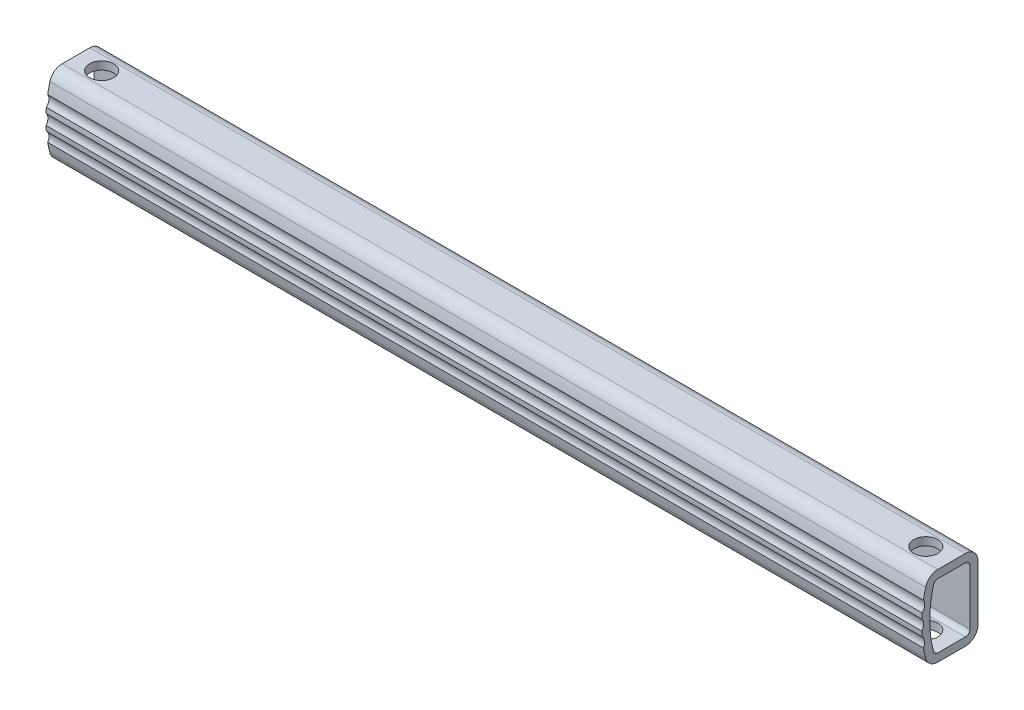
SolidWorks part; units mm, degrees
ref_plane "Front Plane" through (0, 0, 0) normal (0, 0, 1) x (1, 0, 0)
ref_plane "Top Plane" through (0, 0, 0) normal (0, 1, 0) x (1, 0, 0)
ref_plane "Right Plane" through (0, 0, 0) normal (1, 0, 0) x (0, 0, -1)
sketch "Sketch1" plane through (0, 0, 0) normal (1, 0, 0) x (0, 0, -1)
  line L0 (0, 0) -> (-81.198, 0) construction
  line L1 (-1.716, 5) -> (1.716, 5)
  line L2 (3.284, 3.432) -> (3.284, -3.432)
  line L3 (-1.716, -5) -> (1.716, -5)
  line L4 (11.2701, 0) -> (-3.9571, 4.0242) construction
  line L5 (-1.716, 4) -> (1.716, 4)
  line L6 (2.284, 3.432) -> (2.284, -3.432)
  line L7 (11.2701, 0) -> (-3.9571, -4.0242) construction
  line L8 (-1.716, -4) -> (1.716, -4)
  arc A0 (-3.716, 0.6453) -> (-3.716, -0.6453) centre (-4.4799, 0) cw
  arc A1 (-3.232, 3.8326) -> (-1.716, 5) centre (-1.716, 3.432) cw
  arc A2 (1.716, 5) -> (3.284, 3.432) centre (1.716, 3.432) cw
  arc A3 (-3.6742, 1.2906) -> (-3.508, 2.5706) centre (-4.3486, 2.029) ccw
  arc A4 (-3.508, 2.5706) -> (-3.232, 3.8326) centre (11.2701, 0) cw
  arc A5 (-3.716, 0.6453) -> (-3.6742, 1.2906) centre (11.2701, 0) cw
  arc A6 (-3.716, -0.6453) -> (-3.6742, -1.2906) centre (11.2701, 0) ccw
  arc A7 (-3.508, -2.5706) -> (-3.232, -3.8326) centre (11.2701, 0) ccw
  arc A8 (-3.6742, -1.2906) -> (-3.508, -2.5706) centre (-4.3486, -2.029) cw
  arc A9 (1.716, -5) -> (3.284, -3.432) centre (1.716, -3.432) ccw
  arc A10 (-3.232, -3.8326) -> (-1.716, -5) centre (-1.716, -3.432) ccw
  arc A11 (-4.4799, 0) -> (-3.9571, 4.0242) centre (11.2701, 0) cw construction
  arc A12 (-2.2652, -3.5771) -> (-2.2652, 3.5771) centre (11.2701, 0) cw
  arc A13 (-2.2652, 3.5771) -> (-1.716, 4) centre (-1.716, 3.432) cw
  arc A14 (1.716, 4) -> (2.284, 3.432) centre (1.716, 3.432) cw
  arc A15 (1.716, -4) -> (2.284, -3.432) centre (1.716, -3.432) ccw
  arc A16 (-2.2652, -3.5771) -> (-1.716, -4) centre (-1.716, -3.432) ccw
  point P12 (2.284, 0)
  point P13 (0, 5)
  point P29 (-4.3486, 2.029)
  dimension "D1" = 1
  dimension "D2" = 7
  dimension "D5" = 15
  dimension "D6" = 0.75
  dimension "D3" = 5
  dimension "D4" = 10
  dimension "D7" = 1
extrude "Extrude1" add sketch "Sketch1" along normal mid plane 109
sketch "Sketch2" plane through (0, 0, 0) normal (0, 1, 0) x (1, 0, 0)
  line L0 (0, 0) -> (0, -13.5446) construction
  circle A0 centre (-51.285, 0) radius 1.5
  circle A1 centre (51.285, 0) radius 1.5
  dimension "D2" = 3
  dimension "D1" = 102.57
extrude "Cut-Extrude1" cut sketch "Sketch2" against normal through all and the other way through all
